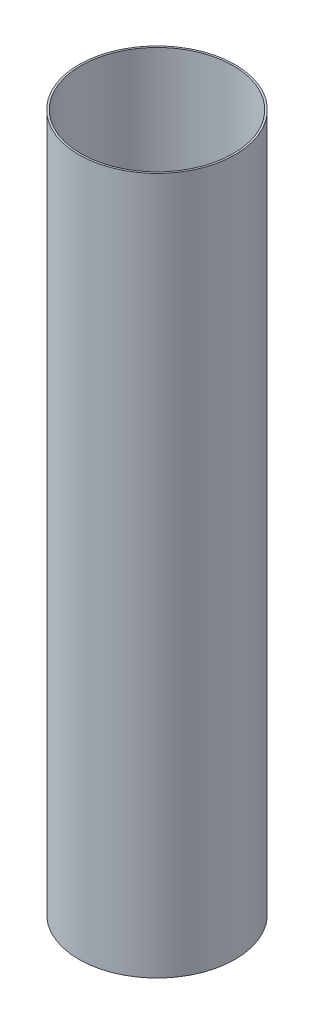
SolidWorks part; units mm, degrees
material "Teak"
ref_plane "Front Plane" through (0, 0, 0) normal (0, 0, 1) x (1, 0, 0)
ref_plane "Top Plane" through (0, 0, 0) normal (0, 1, 0) x (1, 0, 0)
ref_plane "Right Plane" through (0, 0, 0) normal (1, 0, 0) x (0, 0, -1)
sketch "Sketch1" plane through (0, 0, 0) normal (0, 1, 0) x (1, 0, 0)
  circle A0 centre (0, 0) radius 63
  circle A1 centre (0, 0) radius 68
  dimension "D1" = 126
  dimension "D2" = 136
extrude "Boss-Extrude1" add sketch "Sketch1" along normal blind 200
ref_plane "Plane1" through (0, 175, 0) normal (0, 1, 0) x (1, 0, 0)
scale "Scale1" bodies to scale 101 scale about centroid uniform scaling yes scale factor 0.560294
sketch "Sketch2" plane through (0, 156.0294, 0) normal (0, 1, 0) x (1, 0, 0)
  circle A0 centre (0, 0) radius 36.0485
  circle A1 centre (0, 0) radius 35.2985 construction
  circle M2 centre (0, 0) radius 38.1
  dimension "D1" = 0.75
extrude "Cut-Extrude1" cut sketch "Sketch2" against normal blind 10 contours A0 M2
sketch "Sketch3" plane through (0, 43.9706, 0) normal (0, -1, 0) x (1, 0, 0)
  circle A0 centre (0, 0) radius 35.2985
  circle A1 centre (0, 0) radius 38.1
  circle A2 centre (0, 0) radius 35.2985 construction
  circle A3 centre (0, 0) radius 38.1 construction
  dimension "D1" = 70.5971
extrude "Boss-Extrude2" add sketch "Sketch3" along normal blind 237.94
sketch "Sketch4" plane through (0, -193.9694, 0) normal (0, -1, 0) x (1, 0, 0)
  circle A0 centre (0, 0) radius 38.1
  circle A2 centre (0, 0) radius 37.2
  circle A3 centre (0, 0) radius 38.1 construction
  dimension "D1" = 74.4
  dimension "D2" = 0
extrude "Cut-Extrude2" cut sketch "Sketch4" against normal up to surface (349.9988 mm away) contours A2 up to face at (0, 156.0294, 35.2985)
